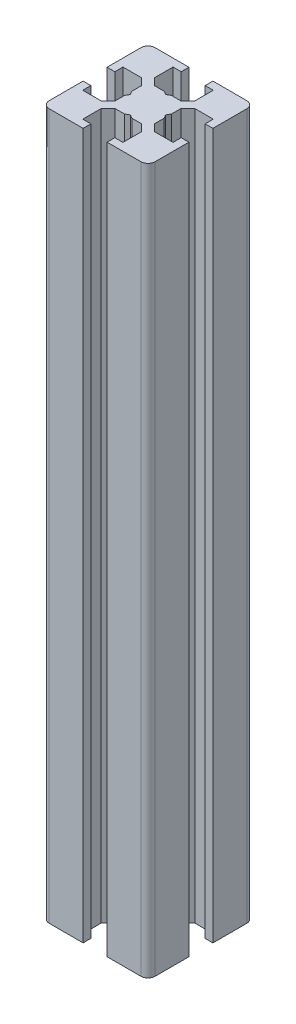
SolidWorks part; units mm, degrees
ref_plane "Front Plane" through (0, 0, 0) normal (0, 0, 1) x (1, 0, 0)
ref_plane "Top Plane" through (0, 0, 0) normal (0, 1, 0) x (1, 0, 0)
ref_plane "Right Plane" through (0, 0, 0) normal (1, 0, 0) x (0, 0, -1)
sketch "Sketch2" plane through (0, 0, 0) normal (0, 1, 0) x (1, 0, 0)
  line L3 (1.7, 7.5) -> (6.5, 7.5)
  line L5 (0, 2.5) -> (-0.5196, 2.8)
  line L6 (-2.85, 3.8) -> (-1.85, 2.8)
  line L9 (1.7, 6.4) -> (1.7, 7.5)
  line L10 (1.7, 6.4) -> (2.85, 6.4)
  line L11 (2.85, 6.4) -> (2.85, 3.8)
  line L12 (2.85, 3.8) -> (1.85, 2.8)
  line L13 (1.85, 2.8) -> (0.5196, 2.8)
  line L14 (2.8, -0.5196) -> (2.8, -1.85)
  line L15 (0, 2.5) -> (0.5196, 2.8)
  line L16 (-2.85, 6.4) -> (-2.85, 3.8)
  line L17 (-1.7, 6.4) -> (-2.85, 6.4)
  line L18 (-1.7, 6.4) -> (-1.7, 7.5)
  line L19 (-1.7, 7.5) -> (-6.5, 7.5)
  line L21 (7.5, -1.7) -> (7.5, -6.5)
  line L22 (6.4, -1.7) -> (7.5, -1.7)
  line L23 (6.4, -1.7) -> (6.4, -2.85)
  line L24 (6.4, -2.85) -> (3.8, -2.85)
  line L25 (2.5, 0) -> (2.8, 0.5196)
  line L26 (0.5196, -2.8) -> (1.85, -2.8)
  line L27 (2.8, 1.85) -> (2.8, 0.5196)
  line L28 (3.8, 2.85) -> (2.8, 1.85)
  line L29 (6.4, 2.85) -> (3.8, 2.85)
  line L30 (6.4, 1.7) -> (6.4, 2.85)
  line L31 (6.4, 1.7) -> (7.5, 1.7)
  line L32 (3.8, -2.85) -> (2.8, -1.85)
  line L33 (2.5, 0) -> (2.8, -0.5196)
  line L34 (7.5, 1.7) -> (7.5, 6.5)
  line L36 (-1.7, -6.4) -> (-1.7, -7.5)
  line L37 (0, -2.5) -> (0.5196, -2.8)
  line L38 (2.85, -3.8) -> (1.85, -2.8)
  line L39 (-1.85, -2.8) -> (-0.5196, -2.8)
  line L41 (0, -2.5) -> (-0.5196, -2.8)
  line L42 (2.85, -6.4) -> (2.85, -3.8)
  line L43 (1.7, -6.4) -> (2.85, -6.4)
  line L44 (1.7, -6.4) -> (1.7, -7.5)
  line L45 (1.7, -7.5) -> (6.5, -7.5)
  line L46 (-1.7, -7.5) -> (-6.5, -7.5)
  line L47 (-1.7, -6.4) -> (-2.85, -6.4)
  line L48 (-2.85, -6.4) -> (-2.85, -3.8)
  line L49 (-2.85, -3.8) -> (-1.85, -2.8)
  line L50 (-7.5, 1.7) -> (-7.5, 6.5)
  line L51 (-6.4, 1.7) -> (-7.5, 1.7)
  line L52 (-6.4, 1.7) -> (-6.4, 2.85)
  line L53 (-6.4, 2.85) -> (-3.8, 2.85)
  line L54 (-2.5, 0) -> (-2.8, -0.5196)
  line L55 (-0.5196, 2.8) -> (-1.85, 2.8)
  line L56 (-2.8, -1.85) -> (-2.8, -0.5196)
  line L57 (-3.8, -2.85) -> (-2.8, -1.85)
  line L58 (-6.4, -2.85) -> (-3.8, -2.85)
  line L59 (-6.4, -1.7) -> (-6.4, -2.85)
  line L60 (-6.4, -1.7) -> (-7.5, -1.7)
  line L61 (-3.8, 2.85) -> (-2.8, 1.85)
  line L62 (-2.5, 0) -> (-2.8, 0.5196)
  line L63 (-7.5, -1.7) -> (-7.5, -6.5)
  line L64 (-2.8, 0.5196) -> (-2.8, 1.85)
  arc A0 (7.5, 6.5) -> (6.5, 7.5) centre (6.5, 6.5) ccw
  arc A1 (-7.5, 6.5) -> (-6.5, 7.5) centre (-6.5, 6.5) cw
  arc A2 (6.5, -7.5) -> (7.5, -6.5) centre (6.5, -6.5) ccw
  arc A3 (-6.5, -7.5) -> (-7.5, -6.5) centre (-6.5, -6.5) cw
  dimension "D11" = 2
  dimension "D2" = 3.4
  dimension "D3" = 5.7
  dimension "D6" = 2.6
  dimension "D7" = 1
  dimension "D8" = 1
extrude "Boss-Extrude1" add sketch "Sketch2" along normal blind 100
